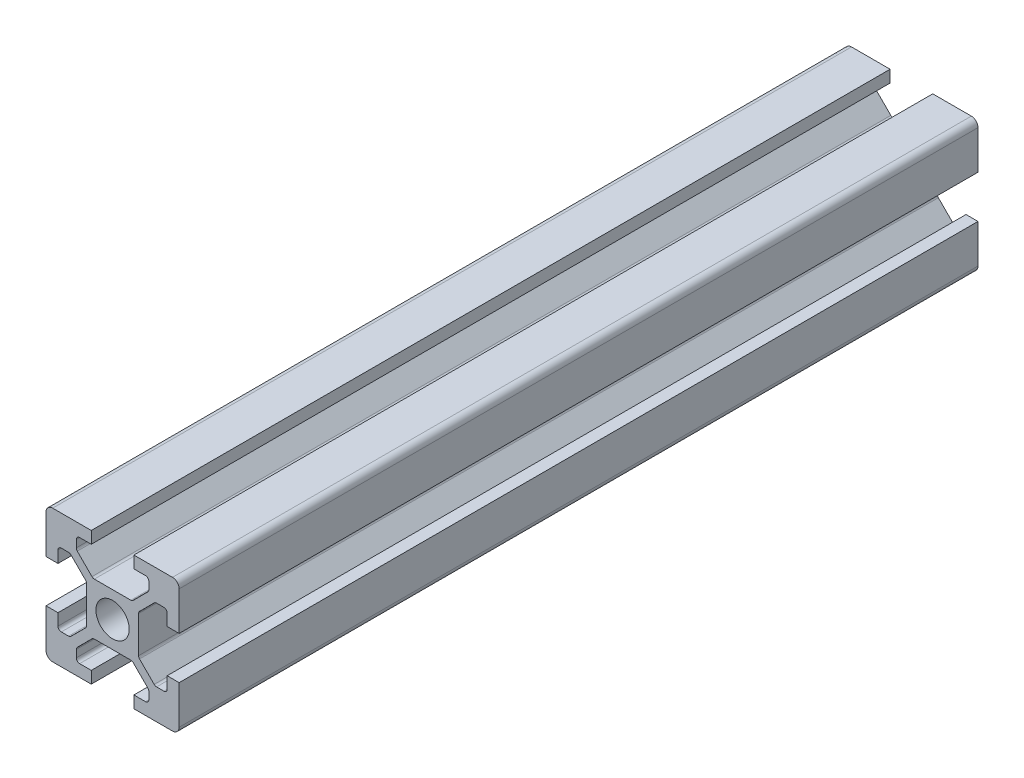
SolidWorks part; units mm, degrees
material "1060 Alloy"
ref_plane "Front Plane" through (0, 0, 0) normal (0, 0, 1) x (1, 0, 0)
ref_plane "Top Plane" through (0, 0, 0) normal (0, 1, 0) x (1, 0, 0)
ref_plane "Right Plane" through (0, 0, 0) normal (1, 0, 0) x (0, 0, -1)
sketch "Sketch1" plane through (0, 0, 0) normal (0, 0, 1) x (1, 0, 0)
  line L0 (20, 0) -> (-8.059, 28.059) construction
  line L1 (0, 0) -> (6.8, 0)
  line L2 (0, 0) -> (0, 6.8)
  line L3 (0, 20) -> (6.8, 20)
  line L4 (20, 0) -> (20, 6.8)
  line L5 (6.8, 20) -> (6.8, 18.2)
  line L6 (20, 20) -> (8.2322, 8.2322) construction
  line L7 (12.95, 6.1) -> (7.05, 6.1)
  line L8 (13.9, 7.05) -> (13.9, 12.95)
  line L9 (12.95, 13.9) -> (7.05, 13.9)
  line L10 (6.1, 7.05) -> (6.1, 12.95)
  line L11 (13.9, 6.1) -> (6.1, 13.9) construction
  line L12 (13.9, 13.9) -> (6.1, 6.1) construction
  line L13 (4.55, 16.4) -> (7.05, 13.9)
  line L14 (13.2, 18.2) -> (13.2, 20)
  line L15 (1.8, 6.8) -> (0, 6.8)
  line L16 (0, 13.2) -> (0, 20)
  line L17 (0, 13.2) -> (1.8, 13.2)
  line L18 (10, 10) -> (10, 13.9) construction
  line L19 (16.4, 4.55) -> (13.9, 7.05)
  line L20 (4.55, 16.4) -> (4.55, 18.2)
  line L21 (4.55, 18.2) -> (6.8, 18.2)
  line L22 (13.2, 18.2) -> (15.45, 18.2)
  line L23 (15.45, 18.2) -> (15.45, 16.4)
  line L24 (15.45, 16.4) -> (12.95, 13.9)
  line L25 (16.4, 4.55) -> (18.2, 4.55)
  line L26 (18.2, 4.55) -> (18.2, 6.8)
  line L27 (20, 6.8) -> (18.2, 6.8)
  line L28 (18.2, 13.2) -> (20, 13.2)
  line L29 (18.2, 13.2) -> (18.2, 15.45)
  line L30 (18.2, 15.45) -> (16.4, 15.45)
  line L31 (16.4, 15.45) -> (13.9, 12.95)
  line L32 (1.8, 4.55) -> (3.6, 4.55)
  line L33 (3.6, 15.45) -> (6.1, 12.95)
  line L34 (3.6, 15.45) -> (1.8, 15.45)
  line L35 (1.8, 15.45) -> (1.8, 13.2)
  line L36 (0, 13.2) -> (1.8, 13.2)
  line L37 (1.8, 6.8) -> (0, 6.8)
  line L38 (3.6, 4.55) -> (6.1, 7.05)
  line L39 (1.8, 6.8) -> (1.8, 4.55)
  line L40 (15.45, 3.6) -> (12.95, 6.1)
  line L41 (4.55, 3.6) -> (7.05, 6.1)
  line L42 (4.55, 1.8) -> (4.55, 3.6)
  line L43 (6.8, 1.8) -> (4.55, 1.8)
  line L44 (6.8, 1.8) -> (6.8, 0)
  line L45 (15.45, 3.6) -> (15.45, 1.8)
  line L46 (15.45, 1.8) -> (13.2, 1.8)
  line L47 (13.2, 0) -> (13.2, 1.8)
  line L48 (13.2, 20) -> (20, 20)
  line L49 (20, 13.2) -> (20, 20)
  line L50 (13.2, 0) -> (20, 0)
  line L51 (6.1, 6.1) -> (-5.5045, -5.5045) construction
  circle A0 centre (10, 10) radius 2.5
  point P25 (10, 16.4)
  point P39 (13.2, 19.1)
  point P46 (0.9, 6.8)
  dimension "D3" = 5
  dimension "D2" = 20
  dimension "D4" = 7.8
  dimension "D5" = 7.8
  dimension "D6" = 6.8
  dimension "D7" = 6.8
  dimension "D8" = 1.8
  dimension "D9" = 10.9
  dimension "D10" = 1.8
  dimension "D11" = 10.9
  dimension "D12" = 20
extrude "Boss-Extrude1" add sketch "Sketch1" along normal blind 120 contours L47 L50 L4 L27 L26 L25 L19 L8 L31 L30 L29 L28 L49 L48 L14 L22 L23 L24 L9 L13 L20 L21 L5 L3 L16 L17 L35 L34 L33 L10 L38 L32 L39 L15 L2 L1 L44 L43 L42 L41 L7 L40 L45 L46 A0
fillet "Fillet1" radius 1 4 edges at (20, 20, 60) (20, 0, 60) (0, 0, 60) (0, 20, 60)
fillet "Fillet2" radius 0.5 6 edges at (4.55, 18.2, 60) (4.55, 16.4, 60) (7.05, 13.9, 60) (15.45, 18.2, 60) (15.45, 16.4, 60) (12.95, 13.9, 60)
fillet "Fillet3" radius 0.5 6 edges at (18.2, 15.45, 60) (16.4, 15.45, 60) (13.9, 12.95, 60) (18.2, 4.55, 60) (13.9, 7.05, 60) (16.4, 4.55, 60)
fillet "Fillet4" radius 0.5 6 edges at (1.8, 15.45, 60) (3.6, 15.45, 60) (6.1, 12.95, 60) (3.6, 4.55, 60) (1.8, 4.55, 60) (6.1, 7.05, 60)
fillet "Fillet5" radius 0.5 6 edges at (7.05, 6.1, 60) (4.55, 3.6, 60) (4.55, 1.8, 60) (15.45, 1.8, 60) (15.45, 3.6, 60) (12.95, 6.1, 60)
